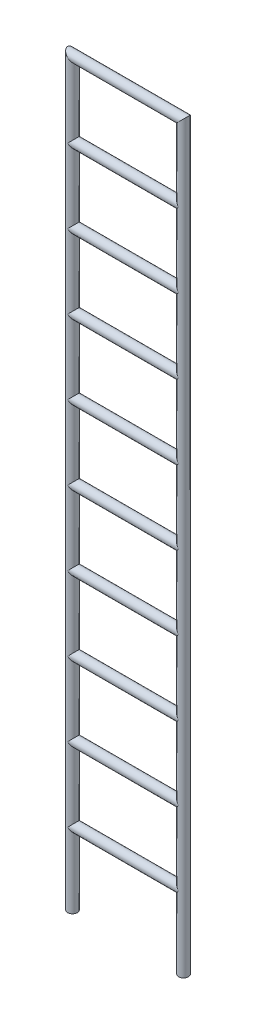
SolidWorks part; units mm, degrees
ref_plane "Front Plane" through (0, 0, 0) normal (0, 0, 1) x (1, 0, 0)
ref_plane "Top Plane" through (0, 0, 0) normal (0, 1, 0) x (1, 0, 0)
ref_plane "Right Plane" through (0, 0, 0) normal (1, 0, 0) x (0, 0, -1)
sketch "Sketch2" plane through (0, 0, 0) normal (0, 0, 1) x (1, 0, 0)
  line L0 (0, -92.3755) -> (0, -3140.3755)
  line L1 (-457.2, -92.3755) -> (-457.2, -3140.3755)
  line L2 (-457.2, -397.1755) -> (0, -397.1755)
  line L3 (-457.2, -1616.3755) -> (0, -1616.3755)
  line L4 (-457.2, -2530.7755) -> (0, -2530.7755)
  line L5 (-457.2, -701.9755) -> (0, -701.9755)
  line L6 (-457.2, -2225.9755) -> (0, -2225.9755)
  line L7 (-457.2, -1006.7755) -> (0, -1006.7755)
  line L8 (-457.2, -1311.5755) -> (0, -1311.5755)
  line L9 (-457.2, -1921.1755) -> (0, -1921.1755)
  line L10 (-457.2, -92.3755) -> (0, -92.3755)
  line L11 (-457.2, -2835.5755) -> (0, -2835.5755)
  point P0 (0, -3140.3755)
  point P15 (285.3754, -2589.9215)
  point P26 (-228.6, -1616.3755)
  dimension "D1" = 3048
  dimension "D2" = 457.2
  dimension "D3" = 304.8
  dimension "D4" = 304.8
  dimension "D5" = 304.8
  dimension "D6" = 304.8
  dimension "D7" = 304.8
  dimension "D8" = 304.8
  dimension "D9" = 304.8
  dimension "D10" = 304.8
  dimension "D11" = 3048
sketch "Sketch3" plane through (0, 0, 0) normal (0, 0, 1) x (1, 0, 0)
  line L0 (0, 0) -> (0, 304.8)
  line L1 (0, 304.8) -> (457.2, 304.8)
  line L2 (457.2, 304.8) -> (457.2, 0)
  point P3 (0, 0)
  point P6 (0, 0)
  dimension "D1" = 457.2
  dimension "D2" = 304.8
sweep "Sweep1" add path "Sketch3" circular profile diameter 40 parameters "D3"=40
pattern_linear "LPattern1" count 10 spacing 304.8 along (0, 1, 0) of "Sweep1"
